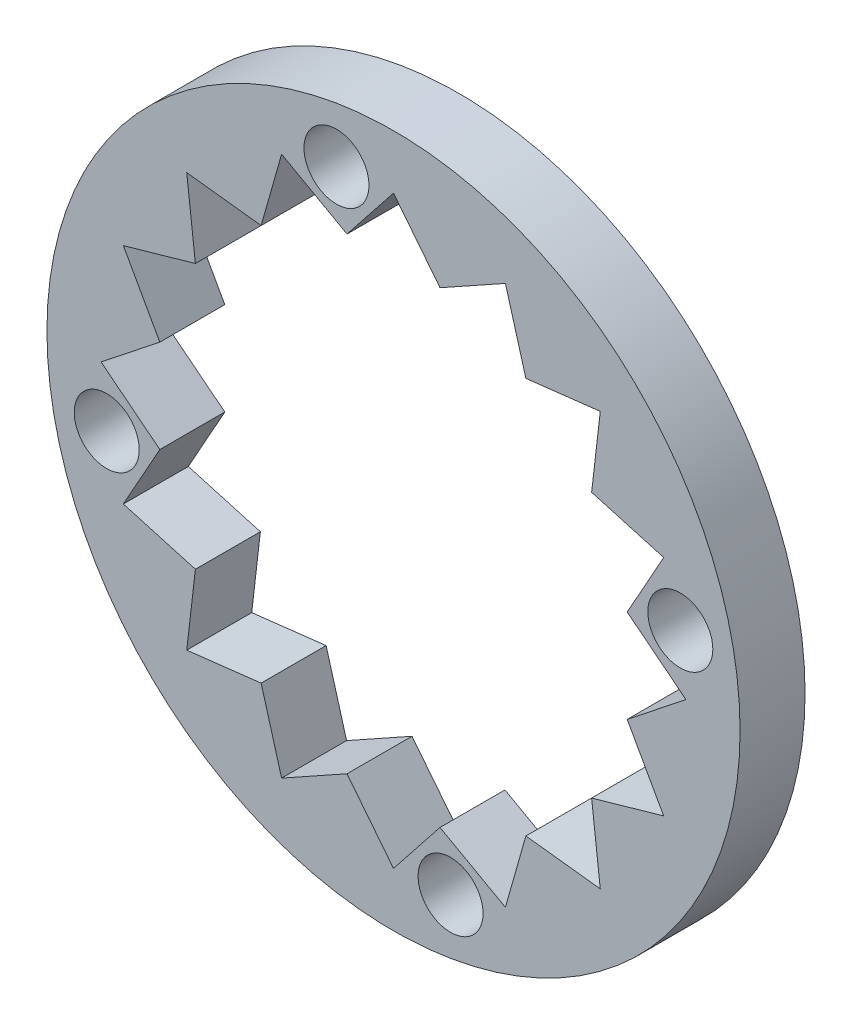
SolidWorks part; units mm, degrees
ref_plane "Plano frontal" through (0, 0, 0) normal (0, 0, 1) x (1, 0, 0)
ref_plane "Plano superior" through (0, 0, 0) normal (0, 1, 0) x (1, 0, 0)
ref_plane "Plano direito" through (0, 0, 0) normal (1, 0, 0) x (0, 0, -1)
sketch "Esboço1" plane through (0, 0, 0) normal (0, 0, 1) x (1, 0, 0)
  line L0 (0, 32) -> (0, -32) construction
  line L1 (-32, 0) -> (32, 0) construction
  line L2 (-22.6274, 22.6274) -> (22.6274, -22.6274) construction
  line L3 (22.6274, 22.6274) -> (-22.6274, -22.6274) construction
  line L4 (-29.5641, 12.2459) -> (29.5641, -12.2459) construction
  line L5 (-29.5641, -12.2459) -> (29.5641, 12.2459) construction
  line L6 (-12.2459, -29.5641) -> (12.2459, 29.5641) construction
  line L7 (12.2459, -29.5641) -> (-12.2459, 29.5641) construction
  line L8 (0, 27) -> (-4.292, 21.5773)
  line L9 (0, 27) -> (4.292, 21.5773)
  line L10 (10.3325, 24.9447) -> (4.292, 21.5773)
  line L11 (10.3325, 24.9447) -> (12.2225, 18.2923)
  line L12 (19.0919, 19.0919) -> (12.2225, 18.2923)
  line L13 (19.0919, 19.0919) -> (18.2923, 12.2225)
  line L14 (24.9447, 10.3325) -> (18.2923, 12.2225)
  line L15 (24.9447, 10.3325) -> (21.5773, 4.292)
  line L16 (27, 0) -> (21.5773, 4.292)
  line L17 (27, 0) -> (21.5773, -4.292)
  line L18 (24.9447, -10.3325) -> (21.5773, -4.292)
  line L19 (24.9447, -10.3325) -> (18.2923, -12.2225)
  line L20 (19.0919, -19.0919) -> (18.2923, -12.2225)
  line L21 (19.0919, -19.0919) -> (12.2225, -18.2923)
  line L22 (10.3325, -24.9447) -> (12.2225, -18.2923)
  line L23 (10.3325, -24.9447) -> (4.292, -21.5773)
  line L24 (0, -27) -> (4.292, -21.5773)
  line L25 (0, -27) -> (-4.292, -21.5773)
  line L26 (-10.3325, -24.9447) -> (-4.292, -21.5773)
  line L27 (-10.3325, -24.9447) -> (-12.2225, -18.2923)
  line L28 (-19.0919, -19.0919) -> (-12.2225, -18.2923)
  line L29 (-19.0919, -19.0919) -> (-18.2923, -12.2225)
  line L30 (-24.9447, -10.3325) -> (-18.2923, -12.2225)
  line L31 (-24.9447, -10.3325) -> (-21.5773, -4.292)
  line L32 (-27, 0) -> (-21.5773, -4.292)
  line L33 (-27, 0) -> (-21.5773, 4.292)
  line L34 (-24.9447, 10.3325) -> (-21.5773, 4.292)
  line L35 (-24.9447, 10.3325) -> (-18.2923, 12.2225)
  line L36 (-19.0919, 19.0919) -> (-18.2923, 12.2225)
  line L37 (-19.0919, 19.0919) -> (-12.2225, 18.2923)
  line L38 (-10.3325, 24.9447) -> (-12.2225, 18.2923)
  line L39 (-10.3325, 24.9447) -> (-4.292, 21.5773)
  circle A0 centre (0, 0) radius 32
  circle A1 centre (0, 0) radius 27
  circle A2 centre (0, 0) radius 22
  point P72 (0, 0)
  dimension "D1" = 64
  dimension "D2" = 54
  dimension "D9" = 5
  dimension "D3" = 45
  dimension "D4" = 45
  dimension "D5" = 22.5
  dimension "D6" = 22.5
  dimension "D7" = 22.5
  dimension "D8" = 22.5
  dimension "D10" = 11.25
  dimension "D11" = 11.25
  dimension "D12" = 16
extrude "Ressalto-extrusão2" add sketch "Esboço1" along normal blind 6 contours A0 A1 | L8 A1 L39 | L38 A1 L37 | L36 A1 L35 | L34 A1 L33 | L32 A1 L31 | L30 A1 L29 | L28 A1 L27 | L26 A1 L25 | L24 A1 L23 | L22 A1 L21 | L20 A1 L19 | L18 A1 L17 | L16 A1 L15 | L14 A1 L13 | L12 A1 L11 | L10 A1 L9
sketch "Esboço3" plane through (0, 0, 6) normal (0, 0, 1) x (1, 0, 0)
  line L0 (-21.5773, -4.292) -> (-26.4812, -5.2674)
  line L1 (21.5773, 4.292) -> (26.4812, 5.2674)
  line L2 (26.4812, 5.2674) -> (31.3851, 6.2429)
  line L3 (-26.4812, -5.2674) -> (-31.3851, -6.2429)
  line L4 (-4.292, 21.5773) -> (-5.2674, 26.4812)
  line L5 (-5.2674, 26.4812) -> (-6.2429, 31.3851)
  line L6 (4.292, -21.5773) -> (5.2674, -26.4812)
  line L7 (5.2674, -26.4812) -> (6.2429, -31.3851)
  line L8 (-18.2923, 12.2225) -> (-22.4497, 15.0004)
  line L9 (-22.4497, 15.0004) -> (-26.607, 17.7782)
  line L10 (18.2923, -12.2225) -> (22.4497, -15.0004)
  line L11 (22.4497, -15.0004) -> (26.607, -17.7782)
  circle A0 centre (-5.2674, 26.4812) radius 3
  circle A1 centre (5.2674, -26.4812) radius 3
  circle A2 centre (26.4812, 5.2674) radius 3
  circle A3 centre (-26.4812, -5.2674) radius 3
  circle A4 centre (0, 0) radius 32 construction
  circle A5 centre (22.4497, -15.0004) radius 3
  circle A6 centre (-22.4497, 15.0004) radius 3
  dimension "D1" = 6
  dimension "D2" = 6
  dimension "D3" = 6
  dimension "D4" = 6
  dimension "D5" = 6
  dimension "D6" = 6
extrude "Corte-extrusão1" cut sketch "Esboço3" against normal through all contours A6 | A0 | A3 | A1 | A5 | A2
sketch "Esboço4" plane through (0, 0, 6) normal (0, 0, 1) x (1, 0, 0)
  circle A0 centre (-22.4497, 15.0004) radius 3
  circle A1 centre (22.4244, -15.2803) radius 3.2811
  point P1 (-22.4497, 15.0004)
  dimension "D2" = 6
extrude "Ressalto-extrusão3" add sketch "Esboço4" against normal blind 6
